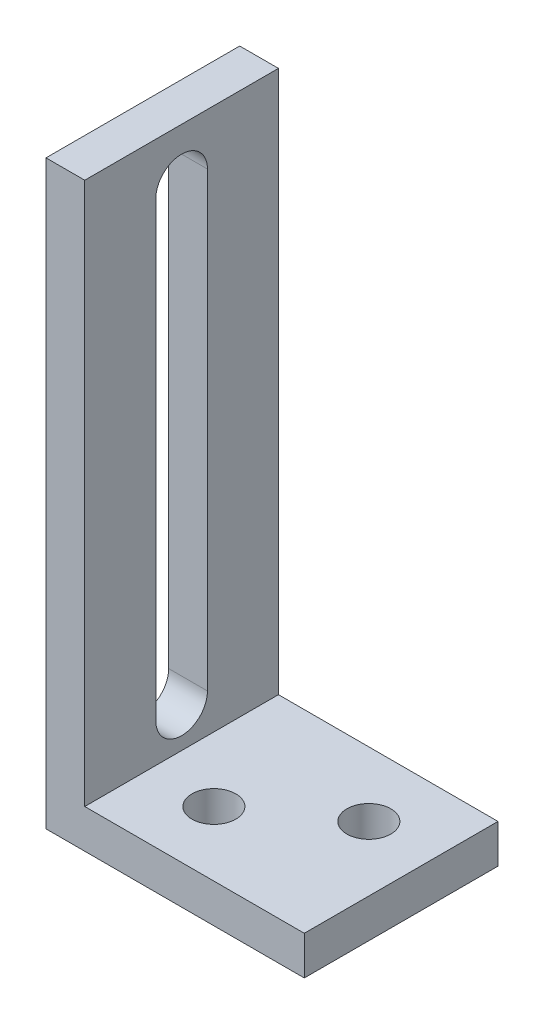
SolidWorks part; units mm, degrees
material "5052-H32"
ref_plane "Front Plane" through (0, 0, 0) normal (0, 0, 1) x (1, 0, 0)
ref_plane "Top Plane" through (0, 0, 0) normal (0, 1, 0) x (1, 0, 0)
ref_plane "Right Plane" through (0, 0, 0) normal (1, 0, 0) x (0, 0, -1)
sketch "Sketch1" plane through (0, 0, 0) normal (0, 0, 1) x (1, 0, 0)
  line L0 (3, 45) -> (3, 3)
  line L1 (0, 0) -> (20, 0)
  line L2 (0, 0) -> (0, 45)
  line L3 (0, 45) -> (3, 45)
  line L4 (20, 0) -> (20, 3)
  line L5 (3, 3) -> (20, 3)
  dimension "D1" = 45
  dimension "D2" = 3
  dimension "D3" = 3
  dimension "D4" = 20
extrude "Boss-Extrude1" add sketch "Sketch1" along normal blind 15
sketch "Sketch2" plane through (0, 0, 0) normal (-1, 0, 0) x (0, 0, 1)
  line L0 (7.5, 0) -> (7.5, 45) construction
  line L1 (15, 0) -> (0, 0) construction
  line L2 (15, 45) -> (0, 45) construction
  line L3 (5.5, 41) -> (5.5, 6)
  line L4 (9.5, 6) -> (9.5, 41)
  circle A0 centre (7.5, 41) radius 2
  circle A1 centre (7.5, 6) radius 2
  dimension "D1" = 4
  dimension "D2" = 4
  dimension "D3" = 35
  dimension "D4" = 6
extrude "Cut-Extrude1" cut sketch "Sketch2" against normal blind 6 contours A1 L0 | L0 A1 | A0 L0 | A1 L0 A0 L3 | L0 A1 L4 A0
sketch "Sketch3" plane through (0, 3, 0) normal (0, 1, 0) x (1, 0, 0)
  line L0 (20, -15) -> (3, -15) construction
  line L2 (0, -15) -> (0, 0) construction
  circle A0 centre (8, -10) radius 1.7
  circle A1 centre (15, -5) radius 1.7
  dimension "D1" = 3.4
  dimension "D2" = 8
  dimension "D3" = 7
  dimension "D5" = 5
  dimension "D4" = 5
extrude "Cut-Extrude2" cut sketch "Sketch3" against normal up to next
